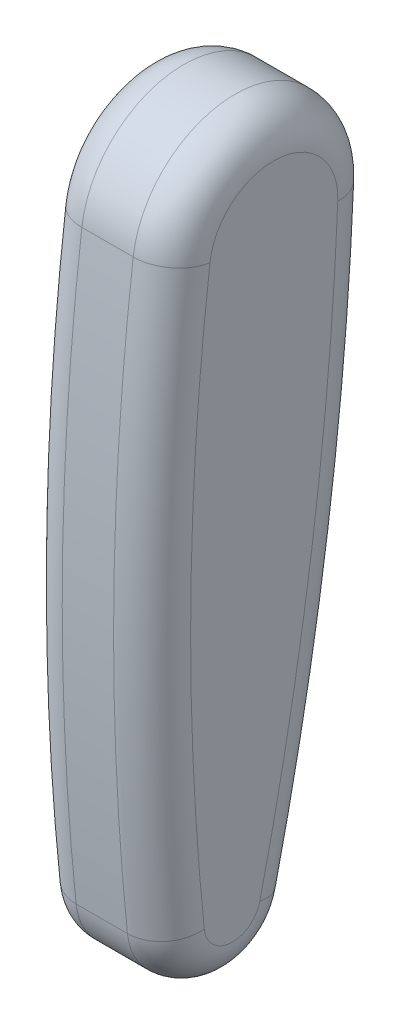
SolidWorks part; units mm, degrees
material "PW90:Mi:0:29:C1:0:1:2:Re:16:"
ref_plane "XY" through (0, 0, 0) normal (0, 0, 1) x (1, 0, 0)
ref_plane "YZ" through (0, 0, 0) normal (0, 1, 0) x (1, 0, 0)
ref_plane "XZ" through (0, 0, 0) normal (1, 0, 0) x (0, 0, -1)
ref_plane "Arm-plane" through (254, 0, 0) normal (1, 0, 0) x (0, 0, -1)
sketch "Sketch5" plane through (254, 0, 0) normal (-1, 0, 0) x (0, 0, 1)
  line L0 (-20.081, -363.1483) -> (-40.4939, -84.495) construction
  arc A0 (9.9184, -78.2306) -> (-91.2484, -86.6439) centre (-40.4939, -84.495) ccw
  arc A1 (-52.2259, -370.6996) -> (12.7609, -366.5734) centre (-20.081, -363.1483) ccw
  arc A2 (12.7609, -366.5734) -> (9.9184, -78.2306) centre (-1250.3885, -234.8403) ccw
  arc A3 (-91.2484, -86.6439) -> (-52.2259, -370.6996) centre (1431.3875, -22.1782) ccw
  dimension "D3" = 1524
  dimension "D4" = 1270
  dimension "D5" = 50.8
  dimension "D6" = 33.02
  dimension "D1" = 279.4
extrude "Base-Extrude" add sketch "Sketch5" along normal mid plane 63.5
fillet "Fillet1" radius 19.05
